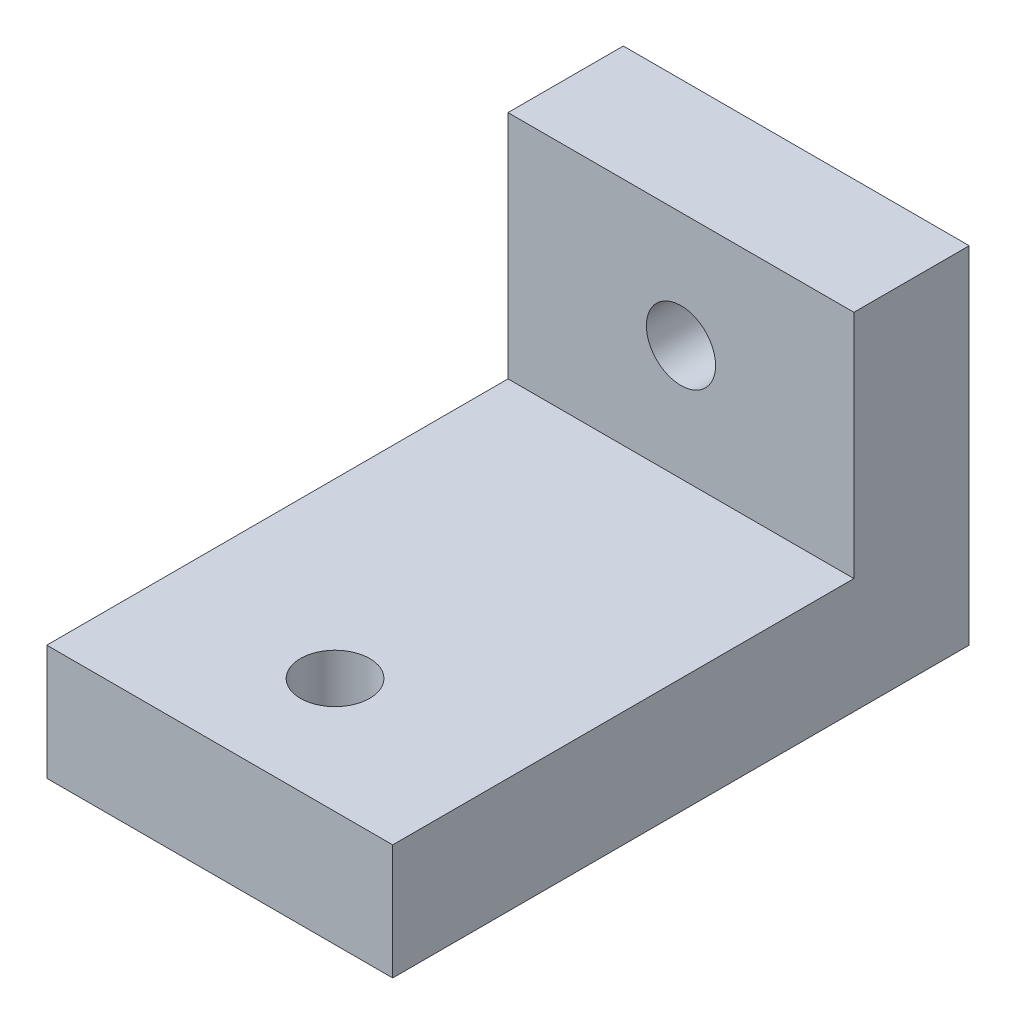
SolidWorks part; units mm, degrees
ref_plane "前视基准面" through (0, 0, 0) normal (0, 0, 1) x (1, 0, 0)
ref_plane "上视基准面" through (0, 0, 0) normal (0, 1, 0) x (1, 0, 0)
ref_plane "右视基准面" through (0, 0, 0) normal (1, 0, 0) x (0, 0, -1)
sketch "Sketch1" plane through (0, 0, 0) normal (0, 1, 0) x (1, 0, 0)
  line L1 (-7.5, 12.5) -> (7.5, 12.5)
  line L2 (-7.5, 12.5) -> (-7.5, -12.5)
  line L3 (-7.5, -12.5) -> (7.5, -12.5)
  line L4 (7.5, 12.5) -> (7.5, -12.5)
  line L5 (-7.5, 12.5) -> (7.5, -12.5) construction
  line L6 (-7.5, -12.5) -> (7.5, 12.5) construction
  point P0 (0, 0)
extrude "Extrude1" add sketch "Sketch1" along normal blind 5
sketch "Sketch2" plane through (0, 5, 0) normal (0, 1, 0) x (1, 0, 0)
  line L0 (7.5, -12.5) -> (7.5, 12.5) construction
  line L1 (-7.5, 12.5) -> (7.5, 12.5)
  line L2 (-7.5, 12.5) -> (-7.5, 7.5)
  line L3 (-7.5, 7.5) -> (7.5, 7.5)
  line L4 (7.5, 12.5) -> (7.5, 7.5)
extrude "Extrude2" add sketch "Sketch2" along normal blind 10
sketch "Sketch3" plane through (0, 5, 0) normal (0, 1, 0) x (1, 0, 0)
  circle A0 centre (0, -7.5) radius 1.5
extrude "Extrude3" cut sketch "Sketch3" against normal blind 10
sketch "Sketch4" plane through (0, 0, -7.5) normal (0, 0, 1) x (1, 0, 0)
  circle A0 centre (0, 10) radius 1.5
extrude "Extrude4" cut sketch "Sketch4" against normal blind 10
